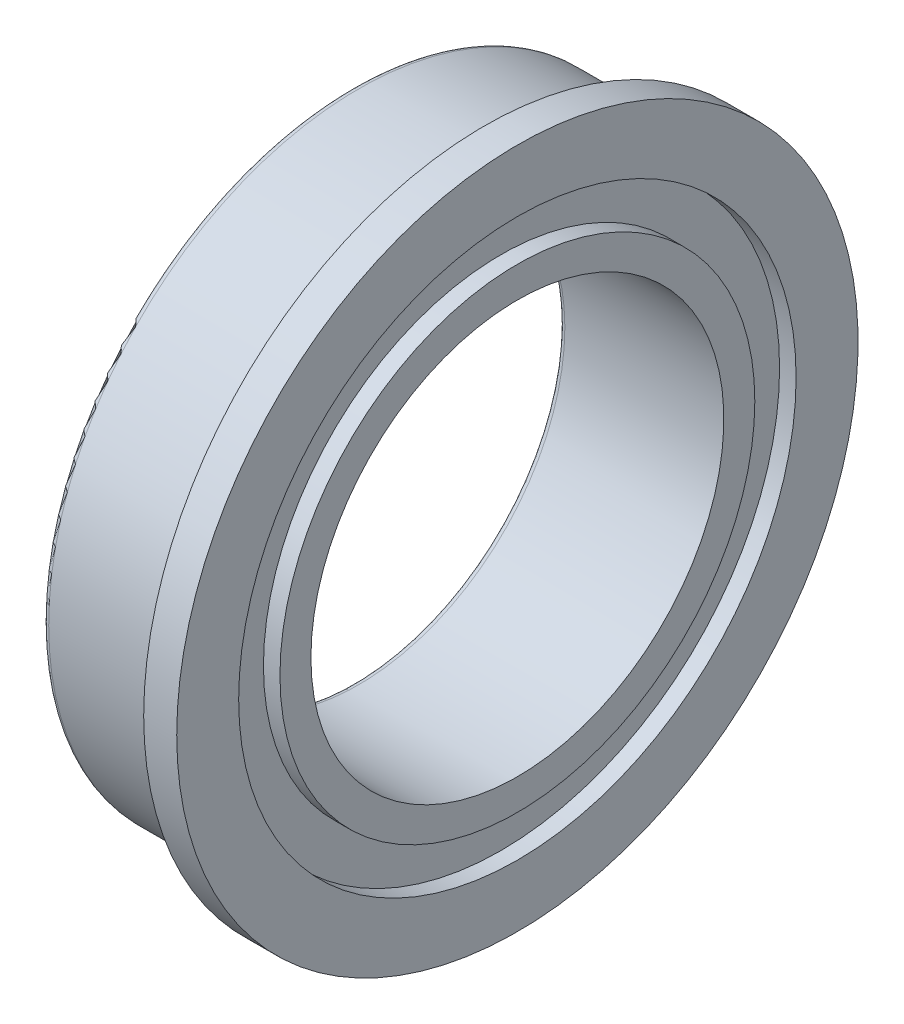
SolidWorks part; units mm, degrees
ref_plane "Front Plane" through (0, 0, 0) normal (0, 0, 1) x (1, 0, 0)
ref_plane "Top Plane" through (0, 0, 0) normal (0, 1, 0) x (1, 0, 0)
ref_plane "Right Plane" through (0, 0, 0) normal (1, 0, 0) x (0, 0, -1)
sketch "Sketch1" plane through (0, 0, 0) normal (0, 0, 1) x (1, 0, 0)
  line L0 (0, -243.0276) -> (0, 11908.3506) construction
  line L1 (-243.0276, 0) -> (11908.3506, 0) construction
  line L10 (2, 8.25) -> (1.2, 8.25)
  line L11 (1.2, 8.25) -> (1.2, 7.5)
  line L12 (1.2, 7.5) -> (-2, 7.5)
  line L13 (-2, 7.5) -> (-2, 6.75)
  line L14 (-2, 6.75) -> (-1.6, 6.75)
  line L15 (-1.6, 6.75) -> (-1.6, 5.75)
  line L16 (-1.6, 5.75) -> (-2, 5.75)
  line L17 (-2, 5.75) -> (-2, 5)
  line L18 (-2, 5) -> (2, 5)
  line L19 (2, 5) -> (2, 5.75)
  line L20 (2, 5.75) -> (1.6, 5.75)
  line L21 (1.6, 5.75) -> (1.6, 6.75)
  line L22 (1.6, 6.75) -> (2, 6.75)
  line L23 (2, 6.75) -> (2, 8.25)
  point P7 (0, 5)
  point P20 (1.7499, 6.9973)
  point P21 (1.4741, 7.5)
  dimension "D1" = 10
  dimension "D2" = 4
  dimension "D3" = 15
  dimension "D4" = 16.5
  dimension "D5" = 0.8
  dimension "D6" = 0.4
  dimension "D7" = 1
revolve "Revolve1" add sketch "Sketch1" angle 360 about L1
fillet "Fillet1" radius 0.15 2 edges at (-2, 0, 7.5) (-2, 0, 5)
